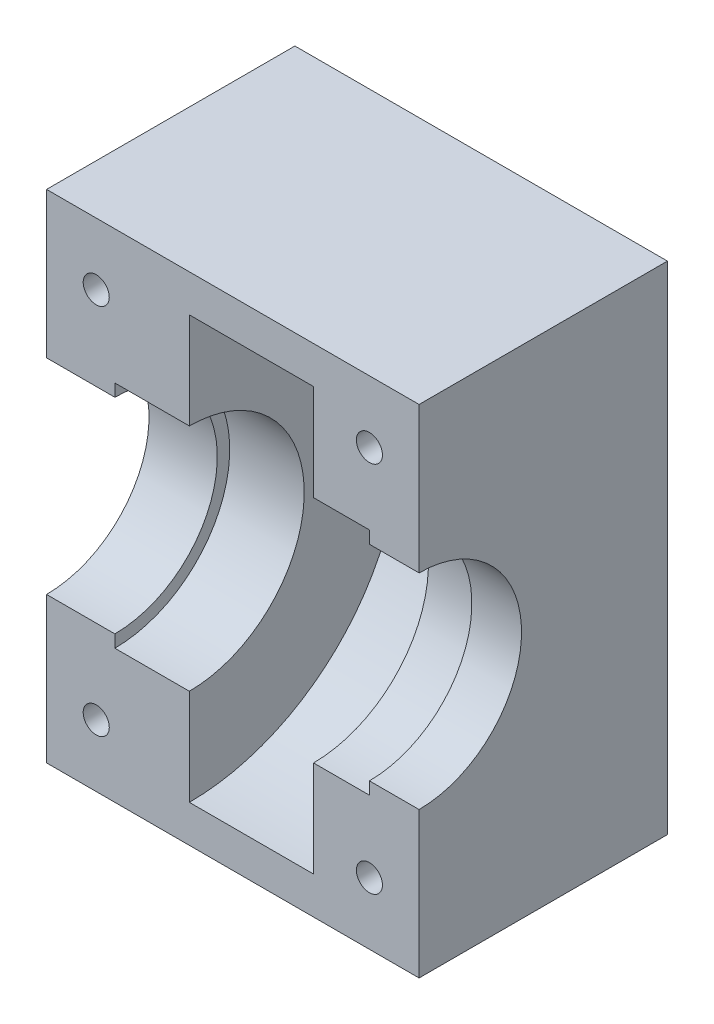
SolidWorks part; units mm, degrees
ref_plane "Piano frontale" through (0, 0, 0) normal (0, 0, 1) x (1, 0, 0)
ref_plane "Piano superiore" through (0, 0, 0) normal (0, 1, 0) x (1, 0, 0)
ref_plane "Piano destro" through (0, 0, 0) normal (1, 0, 0) x (0, 0, -1)
sketch "Schizzo1" plane through (0, 0, 0) normal (0, 0, 1) x (1, 0, 0)
  line L1 (30, -40) -> (-30, -40)
  line L2 (30, -40) -> (30, 40)
  line L3 (30, 40) -> (-30, 40)
  line L4 (-30, -40) -> (-30, 40)
  line L5 (30, -40) -> (-30, 40) construction
  line L6 (30, 40) -> (-30, -40) construction
  point P0 (0, 0)
  dimension "D1" = 80
  dimension "D2" = 60
extrude "Estrusione-Estrusione1" add sketch "Schizzo1" along normal blind 40
sketch "Schizzo3" plane through (-30, 0, 0) normal (-1, 0, 0) x (0, 0, 1)
  line L0 (0, 0) -> (40, 0) construction
  line L1 (0, 40) -> (0, -40) construction
  line L2 (40, 40) -> (40, -40) construction
  circle A0 centre (40, 0) radius 16.5
  dimension "D1" = 33
extrude "Taglio-Estrusione1" cut sketch "Schizzo3" against normal blind 11
sketch "Schizzo4" plane through (-19, 0, 0) normal (-1, 0, 0) x (0, 0, 1)
  line L0 (40, 16.5) -> (40, -16.5) construction
  circle A0 centre (40, 0) radius 18.5
  dimension "D1" = 37
extrude "Taglio-Estrusione2" cut sketch "Schizzo4" against normal blind 12
sketch "Schizzo5" plane through (-7, 0, 0) normal (-1, 0, 0) x (0, 0, 1)
  line L0 (40, 18.5) -> (40, -18.5) construction
  circle A0 centre (40, 0) radius 34
  dimension "D1" = 68
extrude "Taglio-Estrusione3" cut sketch "Schizzo5" against normal blind 20
sketch "Schizzo6" plane through (13, 0, 0) normal (-1, 0, 0) x (0, 0, 1)
  line L0 (40, 34) -> (40, -34) construction
  circle A0 centre (40, 0) radius 18.5
  dimension "D1" = 37
extrude "Taglio-Estrusione4" cut sketch "Schizzo6" against normal blind 9
sketch "Schizzo7" plane through (22, 0, 0) normal (-1, 0, 0) x (0, 0, 1)
  line L0 (40, 18.5) -> (40, -18.5) construction
  circle A0 centre (40, 0) radius 16.5
  dimension "D1" = 33
extrude "Taglio-Estrusione5" cut sketch "Schizzo7" against normal blind 8
sketch "Schizzo8" plane through (0, 0, 40) normal (0, 0, 1) x (1, 0, 0)
  line L0 (-30, 40) -> (-30, 16.5) construction
  line L1 (30, 40) -> (-30, 40) construction
  circle A1 centre (-22, 30) radius 2.5
  dimension "D1" = 5
  dimension "D2" = 8
  dimension "D3" = 10
hole_wizard "Foro filettato M5-1" positions "Schizzo3D1" profile "Schizzo9" tap size "M5" standard "ISO"
sketch3d "Schizzo3D1"
  point P0 (-22, 30, 40)
sketch "Schizzo9" plane through (-22, 30, 40) normal (1, 0, 0) x (0, -1, 0)
  line L0 (0, 0) -> (0, 15.2618)
  line L1 (0, 15.2618) -> (2.1, 14)
  line L2 (2.1, 14) -> (2.1, 0)
  line L5 (2.1, 0) -> (0, 0)
  line L10 (0, 15.2618) -> (-2.1, 14) construction
  line L11 (0, -6.35) -> (0, 107.95) construction
  dimension "Tap Drill Dia." = 4.2
  dimension "Tap Drill Depth" = 14
  dimension "Drill Angle" = 118
cosmetic thread "Filettatura del foro1" parameters "D1"=10, "D2"=5
mirror "Specchia1" about plane through (0, 0, 0) normal (0, 1, 0) of "Foro filettato M5-1"
cosmetic thread "Filettatura del foro2" parameters "D1"=10, "D2"=5
mirror "Specchia2" about plane through (0, 0, 0) normal (1, 0, 0) of "Specchia1", "Foro filettato M5-1"
cosmetic thread "Filettatura del foro3" parameters "D1"=10, "D2"=5
cosmetic thread "Filettatura del foro4" parameters "D1"=10, "D2"=5
